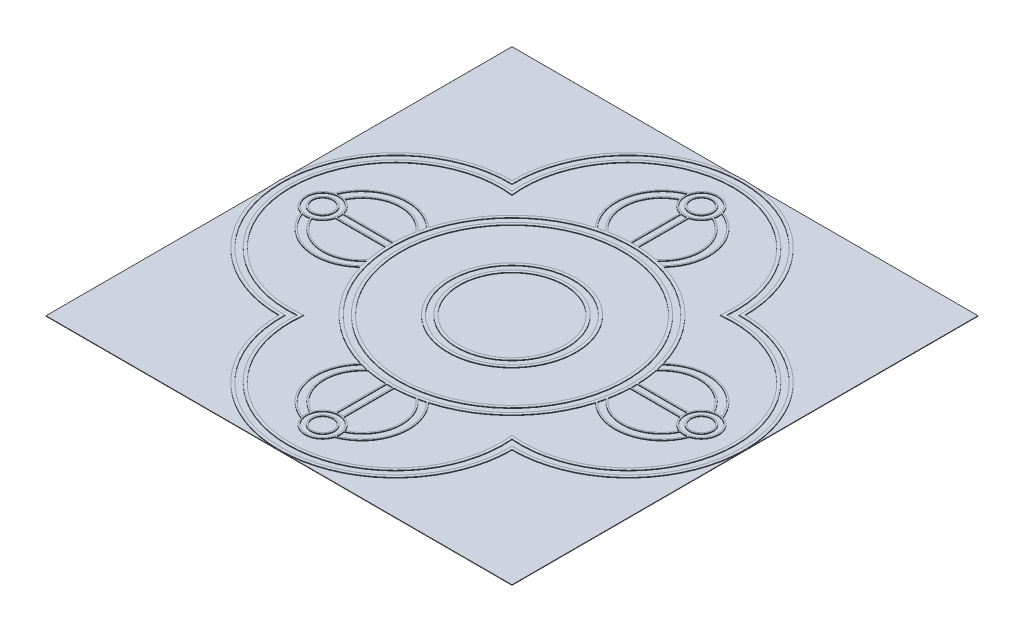
SolidWorks part; units mm, degrees
ref_plane "Front Plane" through (0, 0, 0) normal (0, 0, 1) x (1, 0, 0)
ref_plane "Top Plane" through (0, 0, 0) normal (0, 1, 0) x (1, 0, 0)
ref_plane "Right Plane" through (0, 0, 0) normal (1, 0, 0) x (0, 0, -1)
sketch "Sketch1" plane through (0, 0, 0) normal (0, 1, 0) x (1, 0, 0)
  line L1 (-101.6, -101.6) -> (101.6, -101.6)
  line L2 (-101.6, -101.6) -> (-101.6, 101.6)
  line L3 (-101.6, 101.6) -> (101.6, 101.6)
  line L4 (101.6, -101.6) -> (101.6, 101.6)
  line L5 (-101.6, -101.6) -> (101.6, 101.6) construction
  line L6 (-101.6, 101.6) -> (101.6, -101.6) construction
  point P0 (0, 0)
  dimension "D1" = 203.2
  dimension "D2" = 203.2
extrude "Boss-Extrude1" add sketch "Sketch1" along normal blind 0.2032 contours L1 L4 L3 L2
sketch "Sketch2" plane through (0, 0.2032, 0) normal (0, 1, 0) x (1, 0, 0)
  line L0 (0, 101.6) -> (0, -101.6) construction
  line L1 (-101.6, 101.6) -> (101.6, 101.6) construction
  line L2 (-101.6, -101.6) -> (101.6, -101.6) construction
  line L3 (-101.6, 0) -> (101.6, 0) construction
  line L4 (-101.6, -101.6) -> (-101.6, 101.6) construction
  line L5 (101.6, -101.6) -> (101.6, 101.6) construction
  line L6 (0, 76.2) -> (0, 53.34) construction
  line L7 (-1.27, 75.0366) -> (-1.27, 53.3249)
  line L8 (1.27, 75.0366) -> (1.27, 53.3249)
  line L9 (-1.27, 76.2) -> (-1.27, 53.34) construction
  line L10 (1.27, 76.2) -> (1.27, 53.34) construction
  line L11 (-1.905, 75.172) -> (-1.905, 53.306)
  line L12 (1.905, 75.172) -> (1.905, 53.306)
  line L13 (-1.905, 75.0366) -> (-1.905, 53.34) construction
  line L14 (1.27, 75.0366) -> (1.27, 53.34) construction
  line L15 (1.905, 75.0366) -> (1.905, 53.34) construction
  line L16 (-1.27, 75.0366) -> (-1.27, 53.34) construction
  line L17 (75.0366, 1.27) -> (53.3249, 1.27)
  line L18 (75.0366, -1.27) -> (53.3249, -1.27)
  line L19 (75.172, 1.905) -> (53.306, 1.905)
  line L20 (75.172, -1.905) -> (53.306, -1.905)
  line L21 (76.2, 0) -> (53.34, 0) construction
  line L22 (1.27, -75.0366) -> (1.27, -53.3249)
  line L23 (-1.27, -75.0366) -> (-1.27, -53.3249)
  line L24 (1.905, -75.172) -> (1.905, -53.306)
  line L25 (-1.905, -75.172) -> (-1.905, -53.306)
  line L26 (0, -76.2) -> (0, -53.34) construction
  line L27 (-75.0366, -1.27) -> (-53.3249, -1.27)
  line L28 (-75.0366, 1.27) -> (-53.3249, 1.27)
  line L29 (-75.172, -1.905) -> (-53.306, -1.905)
  line L30 (-75.172, 1.905) -> (-53.306, 1.905)
  line L31 (-76.2, 0) -> (-53.34, 0) construction
  arc A0 (50.8, 50.8) -> (-50.8, 50.8) centre (0, 50.8) ccw
  arc A1 (50.8, -50.8) -> (50.8, 50.8) centre (50.8, 0) ccw
  arc A2 (-50.8, -50.8) -> (50.8, -50.8) centre (0, -50.8) ccw
  arc A3 (-50.8, 50.8) -> (-50.8, -50.8) centre (-50.8, 0) ccw
  arc A4 (-49.5133, 49.5133) -> (-49.5133, -49.5133) centre (-50.8, 0) ccw
  arc A5 (-49.5133, -49.5133) -> (49.5133, -49.5133) centre (0, -50.8) ccw
  arc A6 (49.5133, -49.5133) -> (49.5133, 49.5133) centre (50.8, 0) ccw
  arc A7 (49.5133, 49.5133) -> (-49.5133, 49.5133) centre (0, 50.8) ccw
  arc A8 (46.8213, 46.8213) -> (-46.8213, 46.8213) centre (0, 50.8) ccw
  arc A9 (-46.8213, 46.8213) -> (-46.8213, -46.8213) centre (-50.8, 0) ccw
  arc A10 (-46.8213, -46.8213) -> (46.8213, -46.8213) centre (0, -50.8) ccw
  arc A11 (46.8213, -46.8213) -> (46.8213, 46.8213) centre (50.8, 0) ccw
  arc A12 (45.4, 45.4) -> (-45.4, 45.4) centre (0, 50.8) ccw
  arc A13 (-45.4, 45.4) -> (-45.4, -45.4) centre (-50.8, 0) ccw
  arc A14 (-45.4, -45.4) -> (45.4, -45.4) centre (0, -50.8) ccw
  arc A15 (45.4, -45.4) -> (45.4, 45.4) centre (50.8, 0) ccw
  circle A16 centre (0, 0) radius 50.8 construction
  circle A17 centre (0, 0) radius 25.4 construction
  circle A18 centre (0, 0) radius 26.67
  circle A19 centre (0, 0) radius 52.07
  circle A20 centre (0, 0) radius 24.13
  circle A21 centre (0, 0) radius 49.53
  circle A22 centre (0, 0) radius 53.34
  circle A23 centre (0, 0) radius 27.94
  circle A24 centre (0, 0) radius 48.26
  circle A25 centre (0, 0) radius 22.86
  circle A26 centre (0, 82.55) radius 6.35 construction
  arc A27 (-7.62, 82.55) -> (-12.7, 51.806) centre (0, 65.4992) ccw construction
  arc A28 (7.62, 82.55) -> (12.7, 51.806) centre (0, 65.4992) cw construction
  arc A29 (-6.4224, 83.0362) -> (-12.7, 51.806) centre (0, 65.4992) ccw construction
  arc A30 (-7.483, 83.9884) -> (-14.1402, 51.4316) centre (0, 65.4992) ccw
  circle A31 centre (0, 82.55) radius 7.62
  arc A32 (7.483, 83.9884) -> (14.1402, 51.4316) centre (0, 65.4992) cw
  arc A33 (-7.2976, 84.743) -> (-14.8363, 51.2352) centre (0, 65.4992) ccw
  circle A34 centre (0, 82.55) radius 5.08
  arc A35 (-6.8591, 84.2288) -> (-13.5636, 50.8749) centre (0, 65.4992) ccw construction
  arc A36 (6.8591, 84.2288) -> (13.5636, 50.8749) centre (0, 65.4992) cw construction
  arc A37 (6.4224, 83.0362) -> (12.7, 51.806) centre (0, 65.4992) cw construction
  arc A38 (7.4001, 80.7324) -> (11.1888, 52.1533) centre (0, 65.2107) cw
  arc A39 (-7.4001, 80.7324) -> (-11.1888, 52.1533) centre (0, 65.2107) ccw
  arc A40 (7.2202, 80.1143) -> (10.3932, 52.3176) centre (0, 65.2107) cw
  arc A41 (-7.7212, 84.577) -> (-14.5904, 50.9838) centre (0, 65.4992) ccw construction
  arc A42 (7.1268, 80.1592) -> (10.7756, 52.6355) centre (0, 65.2107) cw construction
  arc A43 (-7.2202, 80.1143) -> (-10.3932, 52.3176) centre (0, 65.2107) ccw
  circle A44 centre (0, 82.55) radius 6.985
  arc A45 (7.2976, 84.743) -> (14.8363, 51.2352) centre (0, 65.4992) cw
  circle A46 centre (0, 82.55) radius 4.445
  arc A47 (7.7212, 84.577) -> (14.5904, 50.9838) centre (0, 65.4992) cw construction
  arc A48 (-7.1268, 80.1592) -> (-10.7756, 52.6355) centre (0, 65.2107) ccw construction
  arc A49 (-7.483, 83.9884) -> (-14.1402, 51.4316) centre (0, 65.4992) ccw construction
  arc A50 (-7.4001, 80.7324) -> (-11.1888, 52.1533) centre (0, 65.2107) ccw construction
  arc A51 (7.4001, 80.7324) -> (11.1888, 52.1533) centre (0, 65.2107) cw construction
  arc A52 (83.9884, 7.483) -> (51.4316, 14.1402) centre (65.4992, 0) ccw
  circle A53 centre (82.55, 0) radius 7.62
  arc A54 (83.9884, -7.483) -> (51.4316, -14.1402) centre (65.4992, 0) cw
  arc A55 (84.743, 7.2976) -> (51.2352, 14.8363) centre (65.4992, 0) ccw
  circle A56 centre (82.55, 0) radius 5.08
  arc A57 (80.7324, -7.4001) -> (52.1533, -11.1888) centre (65.2107, 0) cw
  arc A58 (80.7324, 7.4001) -> (52.1533, 11.1888) centre (65.2107, 0) ccw
  arc A59 (80.1143, -7.2202) -> (52.3176, -10.3932) centre (65.2107, 0) cw
  arc A60 (80.1143, 7.2202) -> (52.3176, 10.3932) centre (65.2107, 0) ccw
  circle A61 centre (82.55, 0) radius 6.985
  arc A62 (84.743, -7.2976) -> (51.2352, -14.8363) centre (65.4992, 0) cw
  circle A63 centre (82.55, 0) radius 4.445
  circle A64 centre (82.55, 0) radius 6.35 construction
  arc A65 (82.55, 7.62) -> (51.806, 12.7) centre (65.4992, 0) ccw construction
  arc A66 (82.55, -7.62) -> (51.806, -12.7) centre (65.4992, 0) cw construction
  circle A67 centre (0, 0) radius 53.34
  arc A68 (7.483, -83.9884) -> (14.1402, -51.4316) centre (0, -65.4992) ccw
  circle A69 centre (0, -82.55) radius 7.62
  arc A70 (-7.483, -83.9884) -> (-14.1402, -51.4316) centre (0, -65.4992) cw
  arc A71 (7.2976, -84.743) -> (14.8363, -51.2352) centre (0, -65.4992) ccw
  circle A72 centre (0, -82.55) radius 5.08
  arc A73 (-7.4001, -80.7324) -> (-11.1888, -52.1533) centre (0, -65.2107) cw
  arc A74 (7.4001, -80.7324) -> (11.1888, -52.1533) centre (0, -65.2107) ccw
  arc A75 (-7.2202, -80.1143) -> (-10.3932, -52.3176) centre (0, -65.2107) cw
  arc A76 (7.2202, -80.1143) -> (10.3932, -52.3176) centre (0, -65.2107) ccw
  circle A77 centre (0, -82.55) radius 6.985
  arc A78 (-7.2976, -84.743) -> (-14.8363, -51.2352) centre (0, -65.4992) cw
  circle A79 centre (0, -82.55) radius 4.445
  circle A80 centre (0, -82.55) radius 6.35 construction
  arc A81 (7.62, -82.55) -> (12.7, -51.806) centre (0, -65.4992) ccw construction
  arc A82 (-7.62, -82.55) -> (-12.7, -51.806) centre (0, -65.4992) cw construction
  circle A83 centre (0, 0) radius 53.34
  arc A84 (-83.9884, -7.483) -> (-51.4316, -14.1402) centre (-65.4992, 0) ccw
  circle A85 centre (-82.55, 0) radius 7.62
  arc A86 (-83.9884, 7.483) -> (-51.4316, 14.1402) centre (-65.4992, 0) cw
  arc A87 (-84.743, -7.2976) -> (-51.2352, -14.8363) centre (-65.4992, 0) ccw
  circle A88 centre (-82.55, 0) radius 5.08
  arc A89 (-80.7324, 7.4001) -> (-52.1533, 11.1888) centre (-65.2107, 0) cw
  arc A90 (-80.7324, -7.4001) -> (-52.1533, -11.1888) centre (-65.2107, 0) ccw
  arc A91 (-80.1143, 7.2202) -> (-52.3176, 10.3932) centre (-65.2107, 0) cw
  arc A92 (-80.1143, -7.2202) -> (-52.3176, -10.3932) centre (-65.2107, 0) ccw
  circle A93 centre (-82.55, 0) radius 6.985
  arc A94 (-84.743, 7.2976) -> (-51.2352, 14.8363) centre (-65.4992, 0) cw
  circle A95 centre (-82.55, 0) radius 4.445
  circle A96 centre (-82.55, 0) radius 6.35 construction
  arc A97 (-82.55, -7.62) -> (-51.806, -12.7) centre (-65.4992, 0) ccw construction
  arc A98 (-82.55, 7.62) -> (-51.806, 12.7) centre (-65.4992, 0) cw construction
  circle A99 centre (0, 0) radius 53.34
  point P297 (0, 0)
  dimension "D1" = 101.6
  dimension "D2" = 1.27
  dimension "D3" = 2.54
  dimension "D4" = 1.27
  dimension "D5" = 101.6
  dimension "D10" = 1.27
  dimension "D6" = 50.8
  dimension "D11" = 12.7
  dimension "D17" = 4
  dimension "D7" = 1.27
  dimension "D12" = 19.05
  dimension "D13" = 12.7
  dimension "D16" = 15.24
  dimension "D8" = 1.27
  dimension "D9" = 1.27
  dimension "D14" = 1.27
  dimension "D15" = 1.27
  dimension "D19" = 0.635
  dimension "D20" = 0.635
extrude "Boss-Extrude2" add sketch "Sketch2" along normal blind 0.254 contours A31 A44 | A43 A31 A39 A22 | A34 A46 | A31 A33 A22 A30 | A31 L11 A22 L7 | A31 L8 A22 L12 | A31 A40 A22 A38 | A45 A31 A32 A22 | A22 A67 A83 A19 | A21 A24 | A53 A55 A22 A52 | A60 A53 A58 A22 | A53 A61 | A53 L19 A22 L17 | A53 L18 A22 L20 | A56 A63 | A53 A59 A22 A57 | A62 A53 A54 A22 | A69 L24 A22 L22 | A69 A77 | A69 L23 A22 L25 | A72 A79 | A76 A69 A74 A67 | A69 A71 A67 A68 | A69 A75 A22 A73 | A78 A69 A70 A67 | A10 A11 A8 A9 A15 A14 A13 A12 | A0 A3 A2 A1 A7 A6 A5 A4 | A20 A25 | A23 A18 | A85 A87 A83 A84 | A92 A85 A90 A83 | A85 A93 | A88 A95 | A85 L28 A22 L30 | A85 L29 A22 L27 | A94 A85 A86 A83 | A85 A91 A22 A89
scale "Scale1" scale about centroid uniform scaling yes scale factor 0.875
